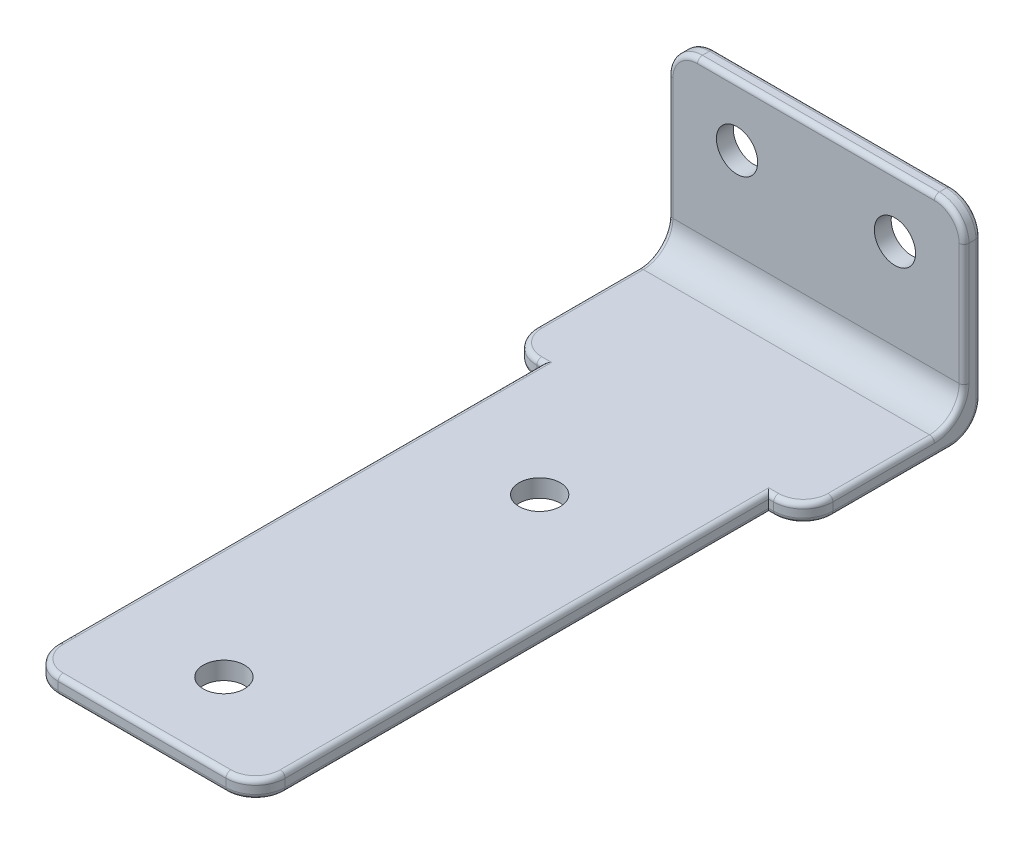
SolidWorks part; units mm, degrees
ref_plane "Front Plane" through (0, 0, 0) normal (0, 0, 1) x (1, 0, 0)
ref_plane "Top Plane" through (0, 0, 0) normal (0, 1, 0) x (1, 0, 0)
ref_plane "Right Plane" through (0, 0, 0) normal (1, 0, 0) x (0, 0, -1)
sketch "Sketch1" plane through (0, 0, 0) normal (0, 1, 0) x (1, 0, 0)
  line L1 (19.05, -44.45) -> (-19.05, -44.45)
  line L2 (19.05, -44.45) -> (19.05, 44.45)
  line L3 (19.05, 44.45) -> (-19.05, 44.45)
  line L4 (-19.05, -44.45) -> (-19.05, 44.45)
  line L5 (19.05, -44.45) -> (-19.05, 44.45) construction
  line L6 (19.05, 44.45) -> (-19.05, -44.45) construction
  point P0 (0, 0)
  dimension "D1" = 88.9
  dimension "D2" = 38.1
extrude "Boss-Base" add sketch "Sketch1" along normal blind 2.286
sketch "Sketch3" plane through (0, 2.286, 0) normal (0, 1, 0) x (1, 0, 0)
  line L0 (19.05, -44.45) -> (19.05, 44.45) construction
  line L1 (-19.05, 44.45) -> (19.05, 44.45)
  line L2 (-19.05, 44.45) -> (-19.05, 42.2783)
  line L3 (-19.05, 42.2783) -> (19.05, 42.2783)
  line L4 (19.05, 44.45) -> (19.05, 42.2783)
  dimension "D1" = 2.1717
extrude "Boss-Lip" add sketch "Sketch3" along normal blind 23.2512
sketch "Base Centerline" plane through (0, 2.286, 0) normal (0, 1, 0) x (1, 0, 0)
  line L0 (0, -44.45) -> (0, 44.45) construction
  line L1 (-19.05, -44.45) -> (19.05, -44.45) construction
  line L2 (19.05, 44.45) -> (-19.05, 44.45) construction
  point P6 (0, -33.9217)
  point P7 (0, 6.7183)
  dimension "D1" = 40.64
  dimension "D2" = 10.5283
hole_wizard "#4 (0.209) Diameter Hole1" positions "Sketch5" profile "Sketch6" hole size "#4" standard "ANSI Inch" end condition through all
sketch "Sketch5" plane through (0, 2.286, 0) normal (0, 1, 0) x (1, 0, 0)
  point P0 (0, -33.9217)
  point P3 (0, 6.7183)
sketch "Sketch6" plane through (0, 2.286, 33.9217) normal (1, 0, 0) x (0, 0, 1)
  line L0 (0, 0) -> (0, 2.286)
  line L1 (0, 2.286) -> (2.6543, 2.286)
  line L2 (2.6543, 2.286) -> (2.6543, 0)
  line L5 (2.6543, 0) -> (0, 0)
  line L11 (0, -6.35) -> (0, 107.95) construction
  dimension "Thru Hole Dia." = 5.3086
  dimension "Thru Hole Depth" = 2.286
sketch "Sketch7" plane through (0, 0, -42.2783) normal (0, 0, 1) x (1, 0, 0)
  line L1 (-19.05, 25.5372) -> (-19.05, 2.286) construction
  line L2 (19.05, 25.5372) -> (19.05, 2.286) construction
  line L3 (19.05, 0) -> (-19.05, 0) construction
  point P0 (10.16, 17.78)
  point P1 (-10.16, 17.78)
  dimension "D1" = 17.78
  dimension "D2" = 8.89
  dimension "D3" = 17.78
  dimension "D4" = 8.89
hole_wizard "#4 (0.209) Diameter Hole2" positions "Sketch7" profile "Sketch8" hole size "#4" standard "ANSI Inch" end condition through all
sketch "Sketch8" plane through (10.16, 17.78, -42.2783) normal (1, 0, 0) x (0, -1, 0)
  line L0 (0, 0) -> (0, 2.1717)
  line L1 (0, 2.1717) -> (2.6543, 2.1717)
  line L2 (2.6543, 2.1717) -> (2.6543, 0)
  line L5 (2.6543, 0) -> (0, 0)
  line L11 (0, -6.35) -> (0, 107.95) construction
  dimension "Thru Hole Dia." = 5.3086
  dimension "Thru Hole Depth" = 2.1717
sketch "Sketch19" plane through (0, 2.286, 0) normal (0, 1, 0) x (1, 0, 0)
  line L0 (0, 44.45) -> (0, -44.45) construction
  line L1 (19.05, -44.45) -> (14.605, -44.45)
  line L2 (19.05, -44.45) -> (19.05, 21.59)
  line L3 (19.05, 21.59) -> (14.605, 21.59)
  line L4 (14.605, -44.45) -> (14.605, 21.59)
  line L6 (-19.05, -44.45) -> (-14.605, -44.45)
  line L7 (-19.05, -44.45) -> (-19.05, 21.59)
  line L8 (-19.05, 21.59) -> (-14.605, 21.59)
  line L9 (-14.605, -44.45) -> (-14.605, 21.59)
  dimension "D1" = 4.445
  dimension "D2" = 66.04
  dimension "D3" = 4.445
  dimension "D4" = 0
extrude "Cut-Extrude1" cut sketch "Sketch19" against normal through all
fillet "Fillet1" radius 3.81 8 edges at (-19.05, 1.143, -21.59) (19.05, 1.143, -21.59) (14.605, 1.143, 44.45) (-14.605, 1.143, 44.45) (-19.05, 25.5372, -43.3641) (19.05, 25.5372, -43.3641) (0, 0, -44.45) (0, 2.286, -42.2783)
fillet "Fillet4" radius 0.635 36 edges at (17.9341, 24.4212, -42.2783) (-17.9341, 24.4212, -42.2783) (17.9341, 24.4212, -44.45) (-17.9341, 24.4212, -44.45) (13.4891, 0, 43.3341) (-13.4891, 0, 43.3341) (13.4891, 2.286, 43.3341) (-13.4891, 2.286, 43.3341) (19.05, 13.9116, -42.2783) (19.05, 12.7686, -44.45) (0, 25.5372, -42.2783) (0, 25.5372, -44.45) (-19.05, 13.9116, -42.2783) (-19.05, 12.7686, -44.45) (0, 0, 44.45) (0, 2.286, 44.45) (14.605, 0, 9.525) (14.605, 2.286, 9.525) (-14.605, 0, 9.525) (-14.605, 2.286, 9.525) (17.9341, 0, -22.7059) (-17.9341, 0, -22.7059) (-17.9341, 2.286, -22.7059) (19.05, 0, -33.02) (-19.05, 0, -33.02) (-19.05, 2.286, -31.9342) (17.9341, 2.286, -22.7059) (19.05, 2.286, -31.9342) (19.05, 1.1159, -43.3341) (-19.05, 1.1159, -43.3341) (19.05, 3.4019, -41.1624) (-19.05, 3.4019, -41.1624) (14.9225, 2.286, -21.59) (-14.9225, 2.286, -21.59) (14.9225, 0, -21.59) (-14.9225, 0, -21.59)
